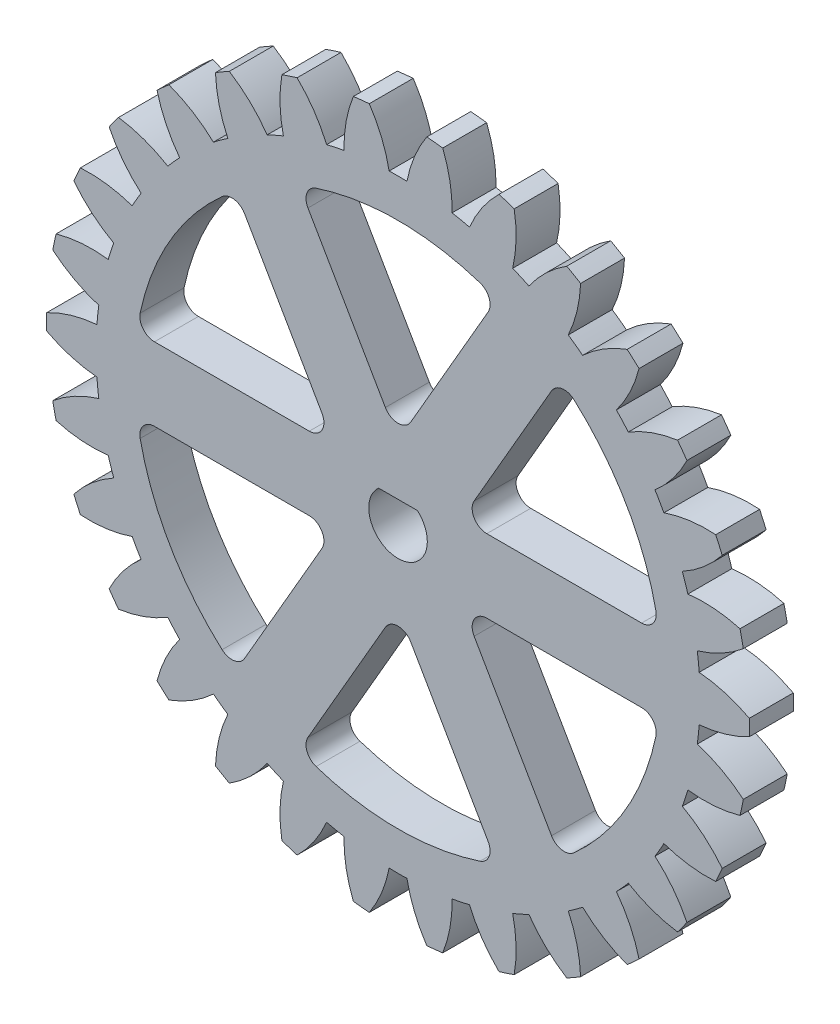
SolidWorks part; units mm, degrees
ref_plane "Front" through (0, 0, 0) normal (0, 0, 1) x (1, 0, 0)
ref_plane "Top" through (0, 0, 0) normal (0, 1, 0) x (1, 0, 0)
ref_plane "Right" through (0, 0, 0) normal (1, 0, 0) x (0, 0, -1)
sketch "Sketch1" plane through (0, 0, 0) normal (0, 0, 1) x (1, 0, 0)
  circle A0 centre (0, 0) radius 24
  dimension "addendumDiameter" = 48
extrude "Boss-Extrude1" add sketch "Sketch1" along normal blind 3
sketch "Sketch2" plane through (0, 0, 3) normal (0, 0, 1) x (1, 0, 0)
  line L0 (0, 0) -> (0, 10.366) construction
  line L1 (0, 0) -> (-0.7698, 7.324) construction
  line L2 (-1.177, 22.4692) -> (-2.3487, 22.346) construction
  circle A0 centre (0, 0) radius 20.625 construction
  circle A1 centre (0, 0) radius 21.1431 construction
  circle A2 centre (0, 0) radius 22.5 construction
  arc A3 (-0.6079, 20.616) -> (0.6079, 20.616) centre (0, 0) cw
  arc A4 (-1.965, 23.9194) -> (1.965, 23.9194) centre (0, 0) cw
  circle A5 centre (0, 0) radius 24 construction
  arc A6 (-1.965, 23.9194) -> (-0.6079, 20.616) centre (-9.4458, 18.9158) cw
  arc A7 (0.6079, 20.616) -> (1.965, 23.9194) centre (9.4458, 18.9158) cw
  circle M1 centre (0, 0) radius 24
  dimension "pitch" = 45
  dimension "baseDiameter" = 42.2862
  dimension "dedendumDiameter" = 41.25
  dimension "flankRadius" = 9
  dimension "halfAngle" = 6
  dimension "halfToothWidth" = 1.1781
extrude "Cut-Extrude1" cut sketch "Sketch2" against normal through all contours A3 A7 A6 M1
pattern_circular "CirPattern1" count 30 over 360 about axis through (0, 0, 0) along (0, 0, 1) of "Cut-Extrude1"
sketch "Sketch3" plane through (0, 0, 3) normal (0, 0, 1) x (1, 0, 0)
  line L0 (0, -28.3666) -> (0, 28.3666) construction
  line L1 (0, 5) -> (-6.7477, 16.6874)
  line L2 (0, 5) -> (6.7477, 16.6874)
  arc A0 (-6.7477, 16.6874) -> (6.7477, 16.6874) centre (0, 0) cw
  point P4 (0, 0)
  dimension "D2" = 18
  dimension "D1" = 60
  dimension "D3" = 5
extrude "Cut-Extrude2" cut sketch "Sketch3" against normal through all
fillet "Fillet1" radius 1 3 edges at (6.7477, 16.6874, 1.5) (0, 5, 1.5) (-6.7477, 16.6874, 1.5)
pattern_circular "CirPattern2" count 6 over 360 about axis through (0, 0, 0) along (0, 0, 1) of "Cut-Extrude2", "Fillet1"
sketch "Sketch4" plane through (0, 0, 3) normal (0, 0, 1) x (1, 0, 0)
  line L0 (-1.3229, 1.5) -> (1.3229, 1.5)
  arc A0 (-1.3229, 1.5) -> (1.3229, 1.5) centre (0, 0) ccw
  dimension "D1" = 4
  dimension "D2" = 1.5
extrude "Cut-Extrude3" cut sketch "Sketch4" against normal through all
equation "\"module\"= 1.5"
equation "\"teeth\"= 30"
equation "\"pressureAngle\"= 20"
equation "\"gearThickness\"= 3"
equation "\"pitch\"= 1 / \"module\""
equation "\"addendumFactor\"= 1"
equation "\"dedendumFactor\"= 1.25"
equation "\"pitchDiameter\"= \"teeth\" / \"pitch\""
equation "\"thickness@Boss-Extrude1\"= \"gearThickness\""
equation "\"addendum\"= \"addendumFactor\" / \"pitch\""
equation "\"addendumDiameter@Sketch1\"= \"pitchDiameter\" + 2 * \"addendum\""
equation "\"D1@CirPattern1\"= \"teeth\""
equation "\"pitch@Sketch2\"= \"pitchDiameter\""
equation "\"dedendum\"= \"dedendumFactor\" / \"pitch\""
equation "\"dedendumDiameter@Sketch2\"= \"pitchDiameter\" - 2 * \"dedendum\""
equation "\"baseDiameter@Sketch2\"= \"pitchDiameter\" * cos ( \"pressureAngle\" / 180 * PI )"
equation "\"flankRadius@Sketch2\"= \"pitchDiameter\" / 5"
equation "\"halfAngle@Sketch2\"= 180 / \"teeth\""
equation "\"halfToothWidth@Sketch2\"= PI / 2 / \"pitch\" / 2"
